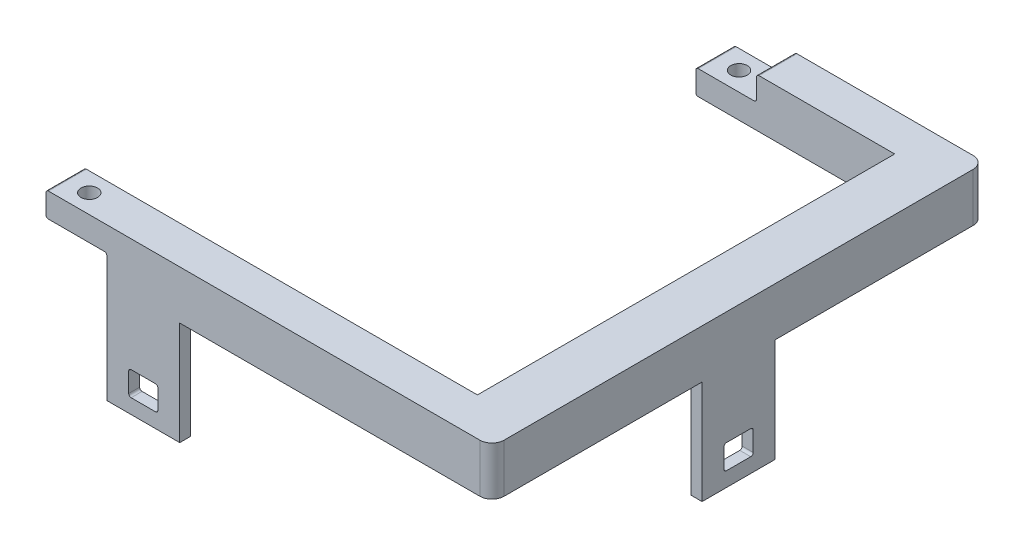
SolidWorks part; units mm, degrees
ref_plane "Front Plane" through (0, 0, 0) normal (0, 0, 1) x (1, 0, 0)
ref_plane "Top Plane" through (0, 0, 0) normal (0, 1, 0) x (1, 0, 0)
ref_plane "Right Plane" through (0, 0, 0) normal (1, 0, 0) x (0, 0, -1)
sketch "Sketch1" plane through (0, 0, 0) normal (0, 1, 0) x (1, 0, 0)
  line L1 (71.7, 50.7) -> (-71.7, 50.7)
  line L2 (71.7, 50.7) -> (71.7, -50.7)
  line L3 (71.7, -50.7) -> (-71.7, -50.7)
  line L4 (-71.7, 50.7) -> (-71.7, -50.7)
  line L5 (71.7, 50.7) -> (-71.7, -50.7) construction
  line L6 (71.7, -50.7) -> (-71.7, 50.7) construction
  point P0 (0, 0)
  dimension "D1" = 143.4
  dimension "D2" = 101.4
extrude "Boss-Extrude1" add sketch "Sketch1" along normal blind 10
sketch "Sketch2" plane through (0, 0, 0) normal (0, -1, 0) x (1, 0, 0)
  line L1 (-60.9, -42.9) -> (60.9, -42.9)
  line L2 (-60.9, -42.9) -> (-60.9, 42.9)
  line L3 (-60.9, 42.9) -> (60.9, 42.9)
  line L4 (60.9, -42.9) -> (60.9, 42.9)
  line L5 (-60.9, -42.9) -> (60.9, 42.9) construction
  line L6 (-60.9, 42.9) -> (60.9, -42.9) construction
  point P0 (0, 0)
  dimension "D1" = 121.8
  dimension "D2" = 85.8
extrude "Cut-Extrude1" cut sketch "Sketch2" against normal through all
sketch "Sketch3" plane through (0, 0, 0) normal (0, -1, 0) x (1, 0, 0)
  line L0 (0, -50.7) -> (0, 50.7) construction
  line L1 (71.7, -50.7) -> (-71.7, -50.7) construction
  line L2 (-71.7, 50.7) -> (71.7, 50.7) construction
  line L3 (-20, 50.7) -> (-20, 42.9)
  line L4 (60.9, 42.9) -> (-60.9, 42.9) construction
  line L5 (20, -42.9) -> (20, -50.7)
  line L6 (-60.9, -42.9) -> (60.9, -42.9) construction
  line L7 (20, -50.7) -> (-71.7, -50.7)
  line L8 (-71.7, -50.7) -> (-71.7, 50.7)
  line L9 (-71.7, 50.7) -> (-20, 50.7)
  line L10 (20, -42.9) -> (-60.9, -42.9)
  line L11 (-60.9, -42.9) -> (-60.9, 42.9)
  line L12 (-60.9, 42.9) -> (-20, 42.9)
  dimension "D1" = 40
extrude "Cut-Extrude2" cut sketch "Sketch3" against normal through all
sketch "Sketch4" plane through (0, 0, 0) normal (0, -1, 0) x (1, 0, 0)
  line L0 (71.7, 50.7) -> (71.7, -50.7) construction
  line L1 (71.7, -7.5) -> (69.45, -7.5)
  line L2 (71.7, -7.5) -> (71.7, 7.5)
  line L3 (71.7, 7.5) -> (69.45, 7.5)
  line L4 (69.45, -7.5) -> (69.45, 7.5)
  line L5 (-20, 50.7) -> (71.7, 50.7) construction
  line L6 (-7.5, 50.7) -> (7.5, 50.7)
  line L7 (-7.5, 50.7) -> (-7.5, 48.45)
  line L8 (-7.5, 48.45) -> (7.5, 48.45)
  line L9 (7.5, 50.7) -> (7.5, 48.45)
  line L10 (0, 0) -> (71.7, 0) construction
  line L11 (0, 0) -> (0, 50.7) construction
  dimension "D1" = 2.25
  dimension "D2" = 15
  dimension "D3" = 15
  dimension "D4" = 2.25
extrude "Boss-Extrude2" add sketch "Sketch4" along normal blind 21.3
sketch "Sketch5" plane through (71.7, 0, 0) normal (1, 0, 0) x (0, 0, -1)
  line L1 (-3, -13.3) -> (3, -13.3)
  line L2 (-3, -13.3) -> (-3, -18.3)
  line L3 (-3, -18.3) -> (3, -18.3)
  line L4 (3, -13.3) -> (3, -18.3)
  line L5 (-3, -13.3) -> (3, -18.3) construction
  line L6 (-3, -18.3) -> (3, -13.3) construction
  line L8 (0, -21.3) -> (0, -11.4736) construction
  line L9 (7.5, -21.3) -> (-7.5, -21.3) construction
  point P0 (0, -15.8)
  dimension "D1" = 6
  dimension "D2" = 5
  dimension "D3" = 3
extrude "Cut-Extrude3" cut sketch "Sketch5" against normal through all
sketch "Sketch6" plane through (0, 0, 50.7) normal (0, 0, 1) x (1, 0, 0)
  line L0 (0, -21.3) -> (0, -9.9463) construction
  line L1 (-3, -13.3) -> (3, -13.3)
  line L2 (-3, -13.3) -> (-3, -18.3)
  line L3 (-3, -18.3) -> (3, -18.3)
  line L4 (3, -13.3) -> (3, -18.3)
  line L5 (-3, -13.3) -> (3, -18.3) construction
  line L6 (-3, -18.3) -> (3, -13.3) construction
  line L7 (7.5, -21.3) -> (-7.5, -21.3) construction
  point P0 (0, -15.8)
  dimension "D1" = 6
  dimension "D2" = 5
  dimension "D3" = 3
extrude "Cut-Extrude4" cut sketch "Sketch6" against normal through all
hole_wizard "M3 Clearance Hole1" positions "Sketch8" profile "Sketch7" hole size "M3" standard "ANSI Metric" end condition through all
sketch "Sketch8" plane through (0, 10, 0) normal (0, 1, 0) x (1, 0, 0)
  line L0 (-20, -42.9) -> (-20, -50.7) construction
  line L1 (20, 50.7) -> (20, 42.9) construction
  line L4 (-20, -46.8) -> (-11.0896, -46.8) construction
  line L6 (20, 46.8) -> (18.0332, 46.8) construction
  point P0 (-15, -46.8)
  point P2 (25, 46.8)
  dimension "D1" = 5
  dimension "D2" = 5
sketch "Sketch7" plane through (-15, 10, 46.8) normal (1, 0, 0) x (0, 0, 1)
  line L0 (0, 0) -> (0, 31.3)
  line L1 (0, 31.3) -> (1.7, 31.3)
  line L2 (1.7, 31.3) -> (1.7, 0)
  line L5 (1.7, 0) -> (0, 0)
  line L11 (0, -6.35) -> (0, 107.95) construction
  dimension "Thru Hole Dia." = 3.4
  dimension "Thru Hole Depth" = 31.3
sketch "Sketch9" plane through (0, 0, 0) normal (0, -1, 0) x (1, 0, 0)
  line L0 (71.7, 50.7) -> (71.7, 7.5) construction
  line L1 (7.5, 50.7) -> (71.7, 50.7)
  line L2 (7.5, 50.7) -> (7.5, 48.45)
  line L3 (7.5, 48.45) -> (69.45, 48.45)
  line L4 (71.7, 50.7) -> (71.7, 7.5)
  line L5 (69.45, 7.5) -> (69.45, 48.45)
  line L6 (69.45, 7.5) -> (71.7, 7.5)
extrude "Boss-Extrude3" [suppressed] add sketch "Sketch9" along normal blind 7
sketch "Sketch10" plane through (0, 0, 50.7) normal (0, 0, 1) x (1, 0, 0)
  line L0 (-20, 10) -> (-20, 0) construction
  line L1 (-20, 5) -> (-7.5, 5)
  line L2 (-20, 5) -> (-20, 0)
  line L3 (-20, 0) -> (-7.5, 0)
  line L4 (-7.5, 5) -> (-7.5, 0)
extrude "Cut-Extrude5" cut sketch "Sketch10" against normal through all
sketch "Sketch11" plane through (0, 0, -50.7) normal (0, 0, -1) x (-1, 0, 0)
  line L0 (-20, 10) -> (-20, 0) construction
  line L1 (-20, 5) -> (-32.5, 5)
  line L2 (-32.5, 5) -> (-32.5, 10)
  line L3 (-71.7, 10) -> (-20, 10) construction
  line L4 (-32.5, 10) -> (-20, 10)
  line L6 (-20, 10) -> (-20, 5)
  dimension "D1" = 12.5
extrude "Cut-Extrude6" cut sketch "Sketch11" against normal up to next
fillet "Fillet1" radius 2.5 2 edges at (71.7, 5, -50.7) (71.7, 5, 50.7)
fillet "Fillet2" radius 0.5 7 edges at (-20, 10, 46.8) (20, 0, -46.8) (32.5, 5, -46.8) (32.5, 10, -46.8) (20, 5, -46.8) (-20, 5, 46.8) (-7.5, 5, 46.8)
fillet "Fillet3" radius 1 2 edges at (0, 0, 48.45) (69.45, 0, 0)
fillet "Fillet4" radius 0.5 8 edges at (70.575, -18.3, -3) (70.575, -18.3, 3) (70.575, -13.3, 3) (70.575, -13.3, -3) (3, -18.3, 49.575) (-3, -18.3, 49.575) (3, -13.3, 49.575) (-3, -13.3, 49.575)
